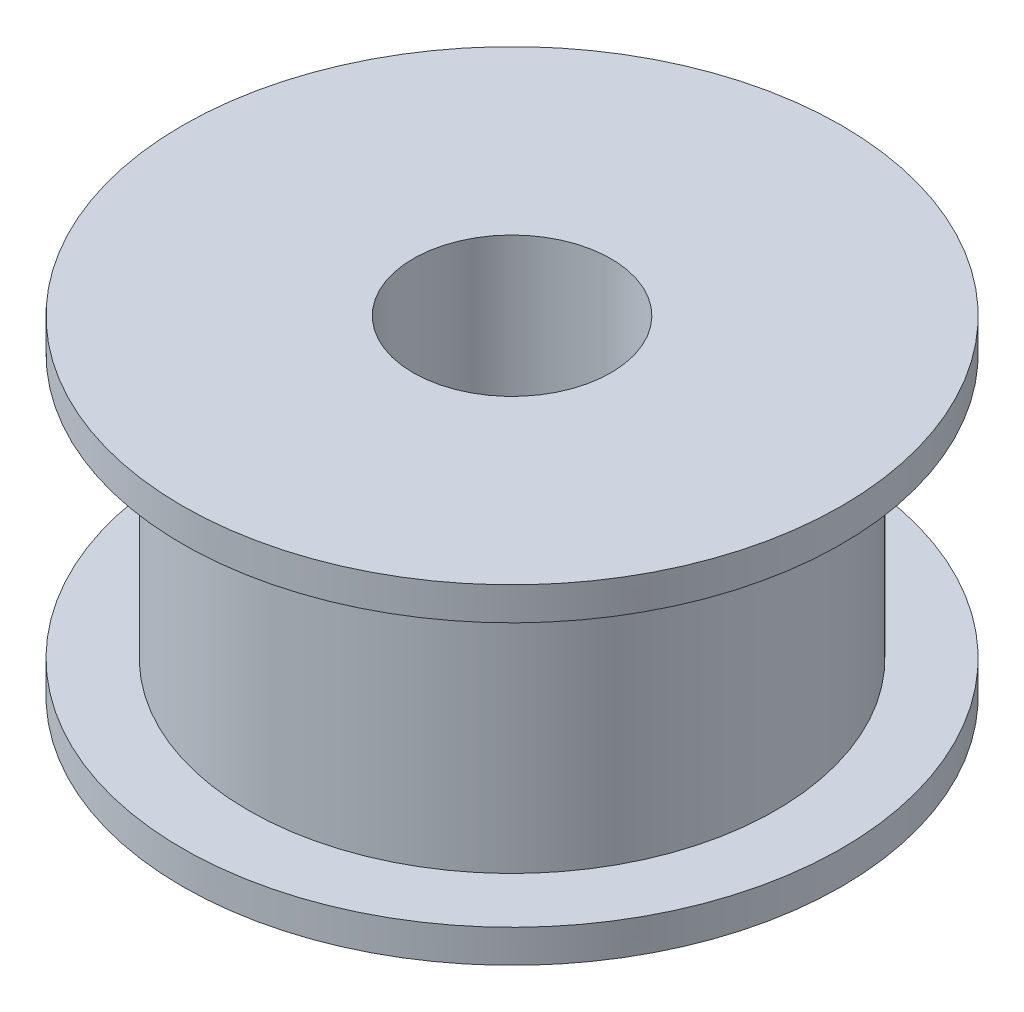
SolidWorks part; units mm, degrees
ref_plane "Front Plane" through (0, 0, 0) normal (0, 0, 1) x (1, 0, 0)
ref_plane "Top Plane" through (0, 0, 0) normal (0, 1, 0) x (1, 0, 0)
ref_plane "Right Plane" through (0, 0, 0) normal (1, 0, 0) x (0, 0, -1)
sketch "Sketch1" plane through (0, 0, 0) normal (0, 1, 0) x (1, 0, 0)
  circle A0 centre (0, 0) radius 5
  circle A1 centre (0, 0) radius 1.5
  dimension "D1" = 3
  dimension "D2" = 10
extrude "Boss-Extrude1" add sketch "Sketch1" along normal mid plane 5
sketch "Sketch2" plane through (0, 0, 0) normal (1, 0, 0) x (0, 0, -1)
  line L0 (-5, -2) -> (-5, 2) construction
  line L1 (-5, 2.5) -> (-5, -2.5) construction
  line L3 (-5, 2) -> (-4, 2) construction
  line L4 (-5, 0) -> (5, 0) construction
  line L5 (5, -2.5) -> (5, 2.5) construction
  line L6 (-5, -2) -> (-4, -2) construction
  line L7 (0, 0) -> (0, 2.5) construction
  line L8 (-4, 2) -> (-5, 2)
  line L9 (-4, 2) -> (-4, -2)
  line L10 (-4, -2) -> (-5, -2)
  line L11 (-5, 2) -> (-5, -2)
  line L12 (-4, 2) -> (-5, -2) construction
  line L13 (-4, -2) -> (-5, 2) construction
  line L14 (5, 2.5) -> (-5, 2.5) construction
  point P11 (-4.5, 0)
  dimension "D1" = 2
  dimension "D2" = 1
revolve "Cut-Revolve1" cut sketch "Sketch2" angle 360 about L7
